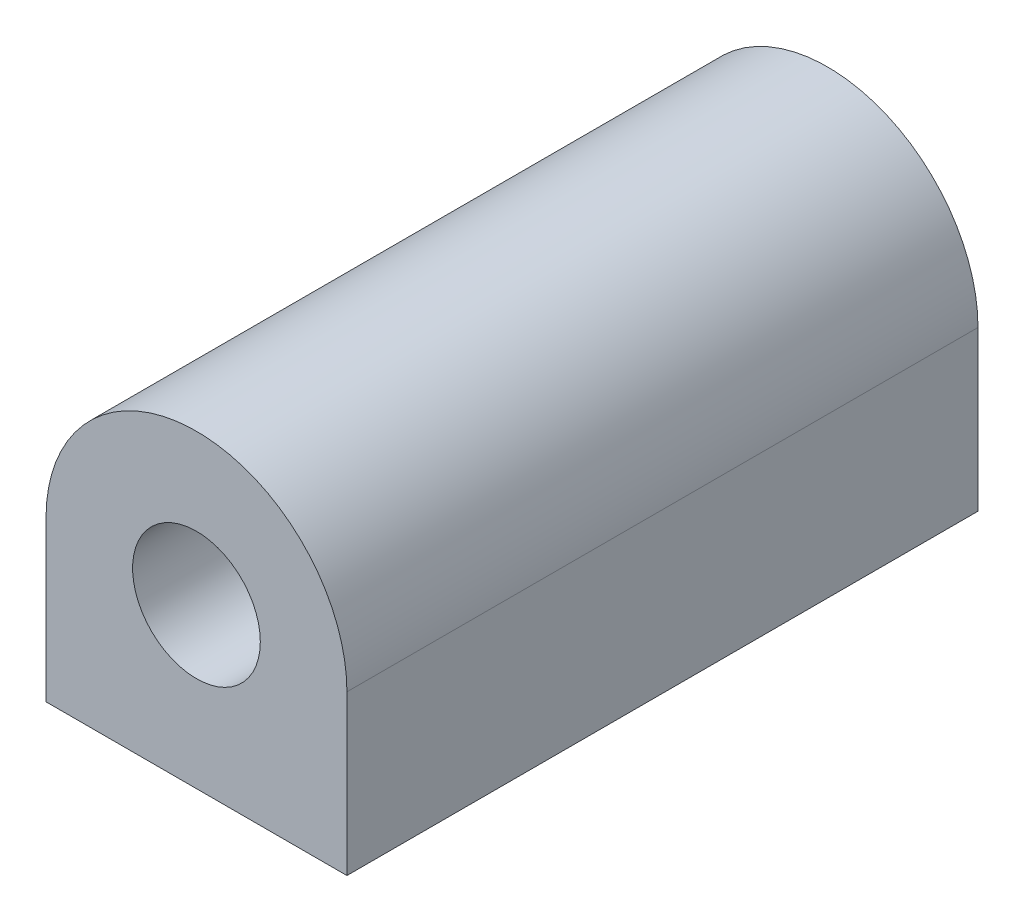
SolidWorks part; units mm, degrees
ref_plane "Front Plane" through (0, 0, 0) normal (0, 0, 1) x (1, 0, 0)
ref_plane "Top Plane" through (0, 0, 0) normal (0, 1, 0) x (1, 0, 0)
ref_plane "Right Plane" through (0, 0, 0) normal (1, 0, 0) x (0, 0, -1)
sketch "Sketch2" plane through (0, 0, 0) normal (0, 0, 1) x (1, 0, 0)
  circle A0 centre (0, 0) radius 1.475
  circle A1 centre (0, 0) radius 3.475
  dimension "D1" = 2.95
  dimension "D2" = 2
extrude "Boss-Extrude2" add sketch "Sketch2" along normal blind 14.575 contours A1
sketch "Sketch3" plane through (0, 0, 14.575) normal (0, 0, 1) x (1, 0, 0)
  circle A0 centre (0, 0) radius 1.475
  dimension "D1" = 2.95
extrude "Cut-Extrude1" cut sketch "Sketch3" against normal blind 10
sketch "Sketch4" plane through (0, 0, 0) normal (0, 0, -1) x (-1, 0, 0)
  circle A0 centre (0, 0) radius 1.475
  dimension "D1" = 2.95
extrude "Cut-Extrude2" cut sketch "Sketch4" against normal blind 10
sketch "Sketch5" plane through (0, 0, 0) normal (0, 0, -1) x (-1, 0, 0)
  line L0 (3.475, 0) -> (3.475, 1.469)
  line L2 (-3.475, 0) -> (3.475, 0)
  line L3 (-3.475, 0) -> (-3.475, -3.475)
  line L4 (-3.475, -3.475) -> (3.475, -3.475)
  line L5 (3.475, 0) -> (3.475, -3.475)
  circle A0 centre (0, 0) radius 3.475
  circle M7 centre (0, 0) radius 3.475
extrude "Boss-Extrude3" add sketch "Sketch5" against normal up to surface (14.575 mm away) contours L3 L4 M7 | L5 L4 M7 up to face at (1.475, 0, 14.575)
sketch "Sketch6" plane through (0, -3.475, 0) normal (0, -1, 0) x (1, 0, 0)
  line L1 (-3.475, 14.575) -> (3.475, 14.575)
  line L2 (-3.475, 14.575) -> (-3.475, 0)
  line L3 (-3.475, 0) -> (3.475, 0)
  line L4 (3.475, 14.575) -> (3.475, 0)
extrude "Boss-Extrude4" add sketch "Sketch6" along normal blind 0.2
